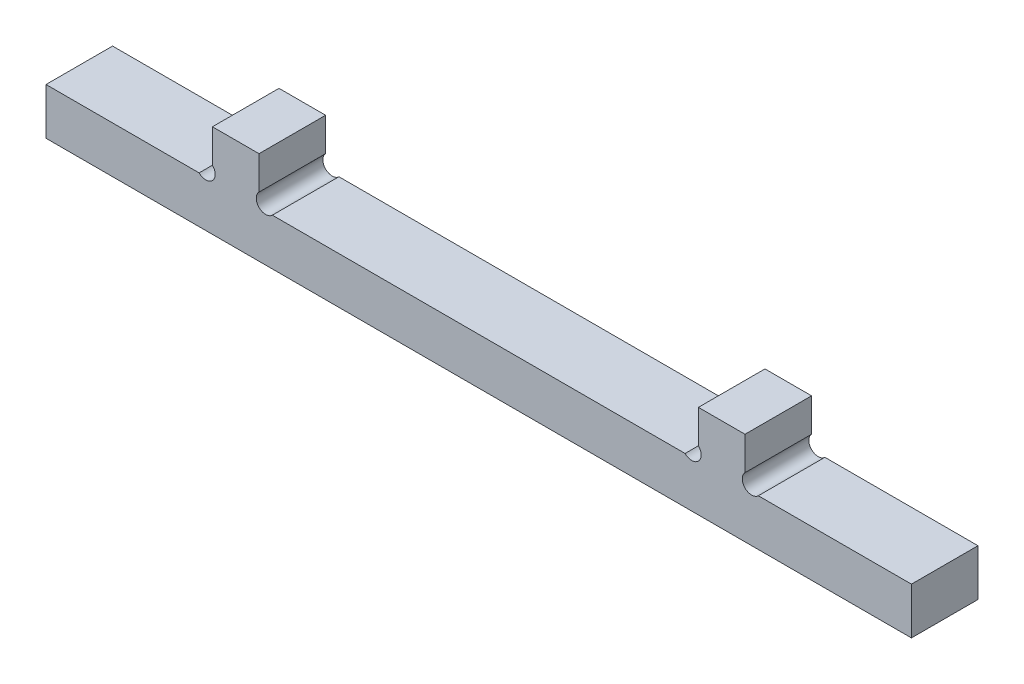
SolidWorks part; units mm, degrees
material "6061 Alloy"
ref_plane "Front Plane" through (0, 0, 0) normal (0, 0, 1) x (1, 0, 0)
ref_plane "Top Plane" through (0, 0, 0) normal (0, 1, 0) x (1, 0, 0)
ref_plane "Right Plane" through (0, 0, 0) normal (1, 0, 0) x (0, 0, -1)
sketch "Sketch1" plane through (0, 0, 0) normal (0, 0, 1) x (1, 0, 0)
  line L0 (0, 0) -> (0, 10.0808) construction
  line L1 (-82.55, 4.445) -> (82.55, 4.445)
  line L2 (-82.55, 4.445) -> (-82.55, -4.445)
  line L3 (-82.55, -4.445) -> (82.55, -4.445)
  line L4 (82.55, 4.445) -> (82.55, -4.445)
  line L5 (-82.55, 4.445) -> (82.55, -4.445) construction
  line L6 (-82.55, -4.445) -> (82.55, 4.445) construction
  line L7 (-50.8, 4.445) -> (-41.91, 4.445)
  line L8 (-50.8, 4.445) -> (-50.8, 13.335)
  line L9 (-50.8, 13.335) -> (-41.91, 13.335)
  line L10 (-41.91, 4.445) -> (-41.91, 13.335)
  line L11 (50.8, 4.445) -> (50.8, 13.335)
  line L12 (50.8, 13.335) -> (41.91, 13.335)
  line L13 (41.91, 4.445) -> (41.91, 13.335)
  line L14 (-46.355, 13.335) -> (-46.355, 4.445) construction
  line L15 (0, 4.445) -> (0, -4.445) construction
  circle A0 centre (-40.64, 5.715) radius 1.7961
  circle A1 centre (-52.07, 5.715) radius 1.7961
  circle A2 centre (52.07, 5.715) radius 1.7961
  circle A3 centre (40.64, 5.715) radius 1.7961
  point P0 (0, 0)
  dimension "D1" = 165.1
  dimension "D2" = 8.89
  dimension "D3" = 31.75
  dimension "D4" = 8.89
  dimension "D5" = 8.89
  dimension "D6" = 101.6
  dimension "D7" = 1.27
  dimension "D8" = 1.27
extrude "Boss-Extrude1" add sketch "Sketch1" along normal blind 12.7 contours L4 L1 L2 L3 | L13 L1 L11 L12 | L1 L10 L9 L8
